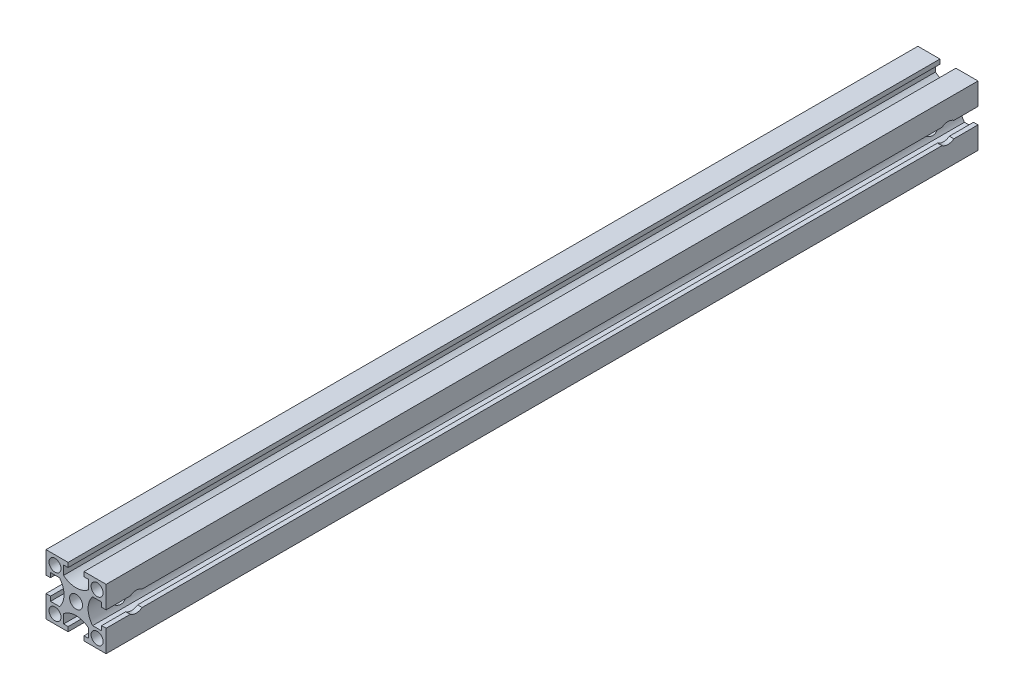
SolidWorks part; units mm, degrees
material "6061-T6 (SS)"
ref_plane "정면" through (0, 0, 0) normal (0, 0, 1) x (1, 0, 0)
ref_plane "윗면" through (0, 0, 0) normal (0, 1, 0) x (1, 0, 0)
ref_plane "우측면" through (0, 0, 0) normal (1, 0, 0) x (0, 0, -1)
sketch "스케치1" plane through (0, 0, 0) normal (0, 0, 1) x (1, 0, 0)
  line L1 (-10, 10) -> (10, 10)
  line L2 (-10, 10) -> (-10, -10)
  line L3 (-10, -10) -> (10, -10)
  line L4 (10, 10) -> (10, -10)
  line L5 (-10, 10) -> (10, -10) construction
  line L6 (-10, -10) -> (10, 10) construction
  point P0 (0, 0)
  dimension "D1" = 20
  dimension "D2" = 20
extrude "보스-돌출1" add sketch "스케치1" along normal blind 290
sketch "스케치2" plane through (0, 0, 290) normal (0, 0, 1) x (1, 0, 0)
  line L0 (-2.65, 10) -> (-2.65, 8.5)
  line L1 (10, 10) -> (-10, 10) construction
  line L2 (-2.65, 8.5) -> (-4.15, 8.5)
  line L3 (-4.15, 8.5) -> (-4.15, 5.5)
  line L4 (-2.65, 10) -> (2.65, 10)
  line L5 (2.65, 10) -> (2.65, 8.5)
  line L6 (2.65, 8.5) -> (4.15, 8.5)
  line L7 (4.15, 8.5) -> (4.15, 5.5)
  line L8 (10, 2.65) -> (8.5, 2.65)
  line L9 (8.5, 2.65) -> (8.5, 4.15)
  line L10 (8.5, 4.15) -> (5.5, 4.15)
  line L11 (10, 2.65) -> (10, -2.65)
  line L12 (10, -2.65) -> (8.5, -2.65)
  line L13 (8.5, -2.65) -> (8.5, -4.15)
  line L14 (8.5, -4.15) -> (5.5, -4.15)
  line L15 (2.65, -10) -> (2.65, -8.5)
  line L16 (2.65, -8.5) -> (4.15, -8.5)
  line L17 (4.15, -8.5) -> (4.15, -5.5)
  line L18 (2.65, -10) -> (-2.65, -10)
  line L19 (-2.65, -10) -> (-2.65, -8.5)
  line L20 (-2.65, -8.5) -> (-4.15, -8.5)
  line L21 (-4.15, -8.5) -> (-4.15, -5.5)
  line L22 (-10, -2.65) -> (-8.5, -2.65)
  line L23 (-8.5, -2.65) -> (-8.5, -4.15)
  line L24 (-8.5, -4.15) -> (-5.5, -4.15)
  line L25 (-10, -2.65) -> (-10, 2.65)
  line L26 (-10, 2.65) -> (-8.5, 2.65)
  line L27 (-8.5, 2.65) -> (-8.5, 4.15)
  line L28 (-8.5, 4.15) -> (-5.5, 4.15)
  arc A1 (-4.15, 5.5) -> (4.15, 5.5) centre (0, 10.4908) ccw
  arc A2 (5.5, 4.15) -> (5.5, -4.15) centre (10.4908, 0) ccw
  arc A3 (4.15, -5.5) -> (-4.15, -5.5) centre (0, -10.4908) ccw
  arc A4 (-5.5, -4.15) -> (-5.5, 4.15) centre (-10.4908, 0) ccw
  circle A5 centre (0, 0) radius 2.15
  circle A6 centre (-7, 7) radius 2
  circle A7 centre (7, 7) radius 2
  circle A8 centre (7, -7) radius 2
  circle A9 centre (-7, -7) radius 2
  point P4 (-2.65, 9.25)
  point P43 (0, 0)
  dimension "D2" = 1.5
  dimension "D8" = 4.3
  dimension "D9" = 4
  dimension "D10" = 4
  dimension "D11" = 4
  dimension "D12" = 4
  dimension "D1" = 5.3
  dimension "D3" = 8.3
  dimension "D4" = 4.15
  dimension "D5" = 2.65
  dimension "D6" = 4
  dimension "D7" = 3
  dimension "D13" = 14
  dimension "D14" = 7
  dimension "D15" = 7
  dimension "D16" = 7
  dimension "D17" = 14
  dimension "D18" = 7
  dimension "D19" = 7
  dimension "D20" = 7
extrude "컷-돌출1" cut sketch "스케치2" against normal through all
sketch "스케치3" plane through (0, 10, 0) normal (0, 1, 0) x (1, 0, 0)
  line L0 (-6.1791, -89.5262) -> (-6.1791, -148.9088) construction
  text T0 "up"
hole_wizard "M6 여유 구멍1" positions "스케치4" profile "스케치5" hole size "M6" standard "KS" end condition through all
sketch "스케치4" plane through (-10, 0, 0) normal (-1, 0, 0) x (0, 0, 1)
  line L0 (290, -10) -> (0, -10) construction
  line L2 (0, 10) -> (0, 2.65) construction
  line L3 (290, -2.65) -> (290, -10) construction
  point P0 (10, 0)
  point P2 (280, 0)
  point P11 (0, -5.1421)
  dimension "D1" = 10
  dimension "D2" = 10
  dimension "D3" = 10
  dimension "D4" = 10
sketch "스케치5" plane through (-10, 0, 10) normal (0, 1, 0) x (0, 0, 1)
  line L0 (0, 0) -> (0, 20)
  line L1 (0, 20) -> (3.3, 20)
  line L2 (3.3, 20) -> (3.3, 0)
  line L5 (3.3, 0) -> (0, 0)
  line L11 (0, -6.35) -> (0, 107.95) construction
  dimension "관통 구멍 지름" = 6.6
  dimension "관통 구멍 깊이" = 20
